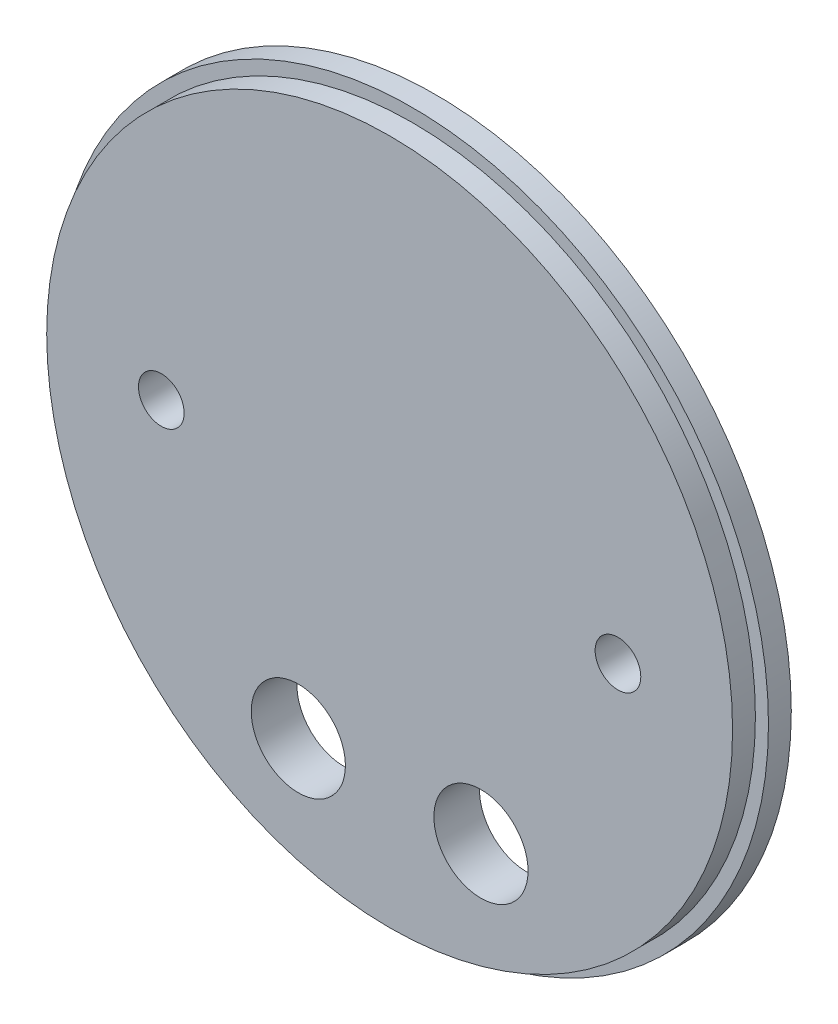
SolidWorks part; units mm, degrees
ref_plane "Front Plane" through (0, 0, 0) normal (0, 0, 1) x (1, 0, 0)
ref_plane "Top Plane" through (0, 0, 0) normal (0, 1, 0) x (1, 0, 0)
ref_plane "Right Plane" through (0, 0, 0) normal (1, 0, 0) x (0, 0, -1)
sketch "Sketch1" plane through (0, 0, 0) normal (0, 0, 1) x (1, 0, 0)
  circle A0 centre (0, 0) radius 49.5046
  point P3 (0, 0)
  dimension "D1" = 99.0092
extrude "Boss-Extrude1" add sketch "Sketch1" along normal blind 3.175
sketch "Sketch2" plane through (0, 0, 3.175) normal (0, 0, 1) x (1, 0, 0)
  circle A0 centre (0, 0) radius 47.6885
  dimension "D1" = 95.377
extrude "Boss-Extrude2" add sketch "Sketch2" along normal blind 3.175
sketch "Sketch3" plane through (0, 0, 6.35) normal (0, 0, 1) x (1, 0, 0)
  circle A0 centre (-12.7, -31.2354) radius 6.5484
  circle A1 centre (-12.7, -31.2354) radius 12.7 construction
  circle A2 centre (-12.7, -31.2354) radius 13.97 construction
  circle A3 centre (12.7, -31.2354) radius 6.5484
  circle A4 centre (12.7, -31.2354) radius 12.7 construction
  circle A5 centre (12.7, -31.2354) radius 13.97 construction
  circle A6 centre (0, 0) radius 47.6885 construction
  circle A7 centre (-31.75, 0) radius 3.175
  circle A8 centre (31.75, 0) radius 3.175
  point P14 (0, 0)
  dimension "D1" = 13.0969
  dimension "D2" = 25.4
  dimension "D3" = 27.94
  dimension "D4" = 63.5
  dimension "D6" = 6.35
  dimension "D5" = 31.75
extrude "Cut-Extrude1" cut sketch "Sketch3" against normal through all
